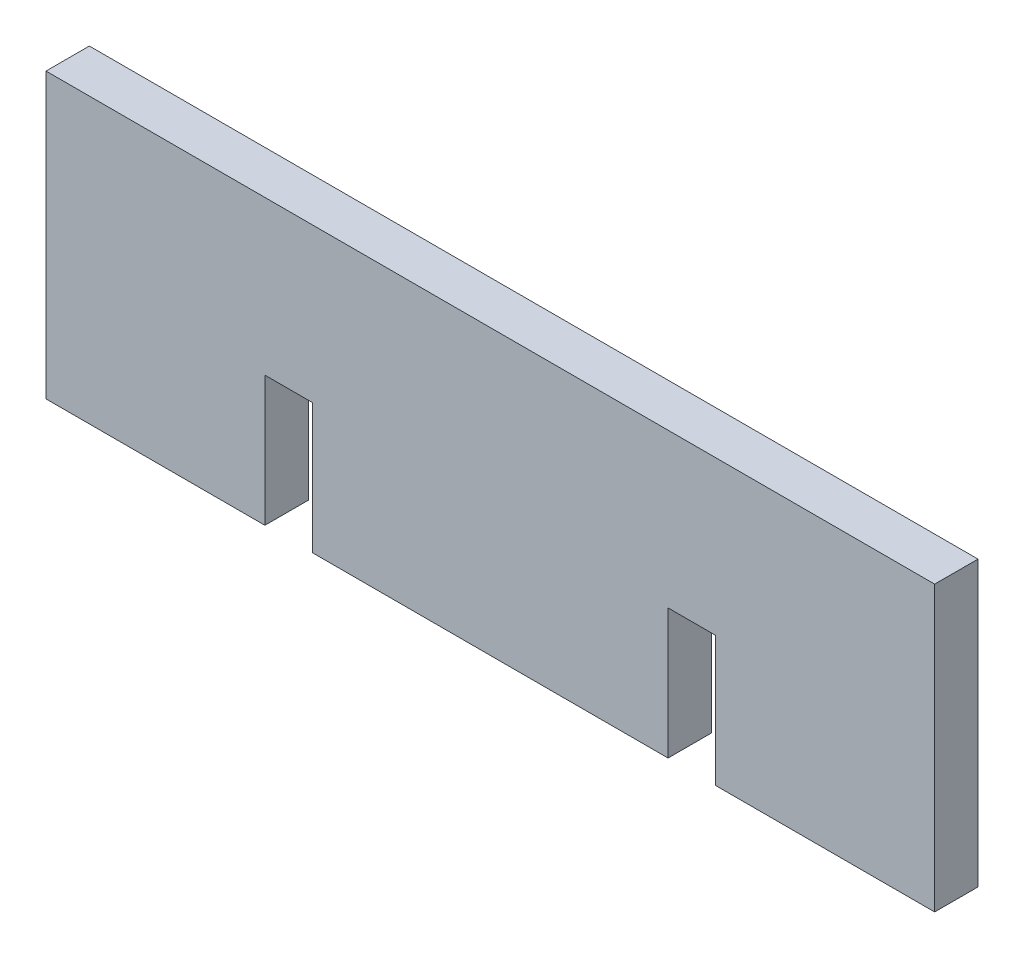
SolidWorks part; units mm, degrees
ref_plane "前视基准面" through (0, 0, 0) normal (0, 0, 1) x (1, 0, 0)
ref_plane "上视基准面" through (0, 0, 0) normal (0, 1, 0) x (1, 0, 0)
ref_plane "右视基准面" through (0, 0, 0) normal (1, 0, 0) x (0, 0, -1)
sketch "草图1" plane through (0, 0, 0) normal (0, 0, 1) x (1, 0, 0)
  line L0 (-41, -32.75) -> (41, -32.75)
  line L1 (-102.5, 32.75) -> (102.5, 32.75)
  line L2 (-102.5, 32.75) -> (-102.5, -32.75)
  line L3 (-102.5, -32.75) -> (-52, -32.75)
  line L4 (102.5, 32.75) -> (102.5, -32.75)
  line L5 (-102.5, 32.75) -> (102.5, -32.75) construction
  line L6 (-102.5, -32.75) -> (102.5, 32.75) construction
  line L7 (41, -32.75) -> (41, -2.75)
  line L8 (41, -2.75) -> (52, -2.75)
  line L9 (52, -2.75) -> (52, -32.75)
  line L10 (-41, -32.75) -> (-41, -2.75)
  line L11 (-41, -2.75) -> (-52, -2.75)
  line L12 (-52, -2.75) -> (-52, -32.75)
  line L13 (-41, -32.75) -> (41, -32.75)
  line L14 (52, -32.75) -> (102.5, -32.75)
  point P0 (0, 0)
  point P9 (0, -32.75)
  dimension "D1" = 205
  dimension "D2" = 65.5
  dimension "D3" = 11
  dimension "D4" = 30
extrude "凸台-拉伸1" add sketch "草图1" along normal blind 10 contours L9 L14 L4 L1 L2 L3 L12 L11 L10 L0 L7 L8
